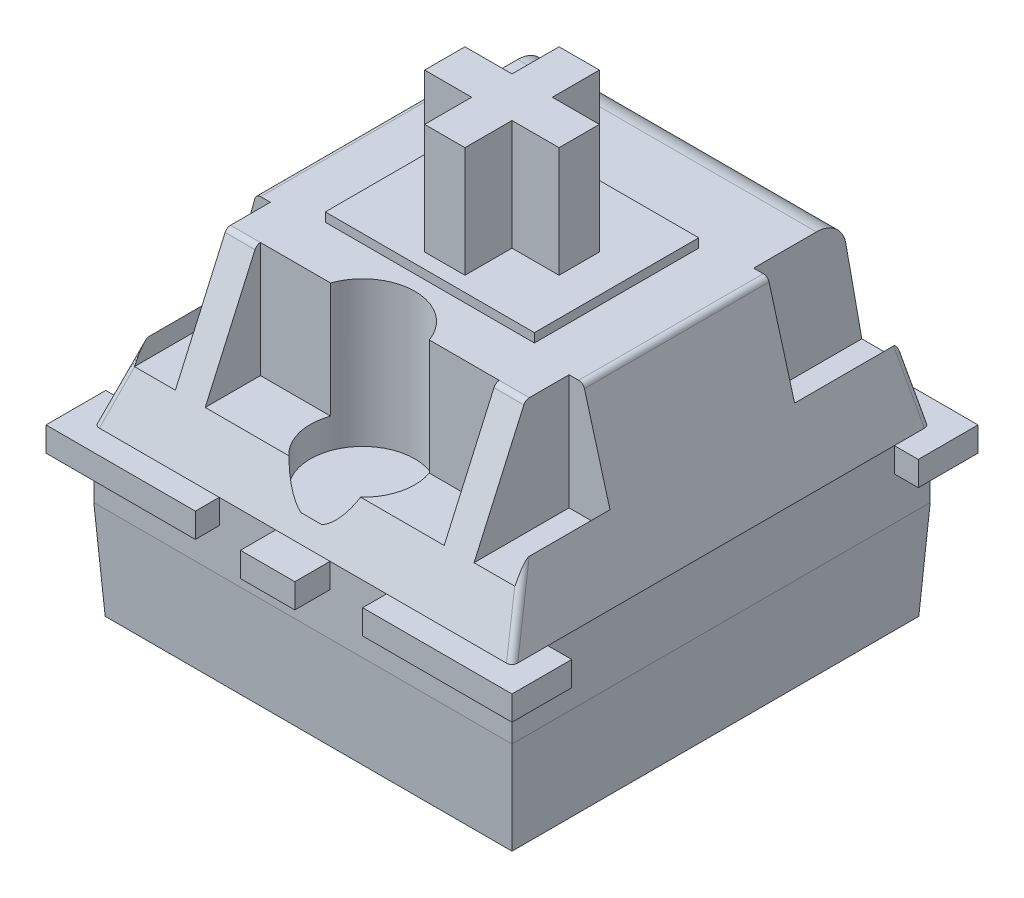
SolidWorks part; units mm, degrees
ref_plane "Front Plane" through (0, 0, 0) normal (0, 0, 1) x (1, 0, 0)
ref_plane "Top Plane" through (0, 0, 0) normal (0, 1, 0) x (1, 0, 0)
ref_plane "Right Plane" through (0, 0, 0) normal (1, 0, 0) x (0, 0, -1)
sketch "Sketch1" plane through (0, 0, 0) normal (0, 1, 0) x (1, 0, 0)
  line L1 (-7, -7) -> (7, -7)
  line L2 (-7, -7) -> (-7, 7)
  line L3 (-7, 7) -> (7, 7)
  line L4 (7, -7) -> (7, 7)
  line L5 (-7, -7) -> (7, 7) construction
  line L6 (-7, 7) -> (7, -7) construction
  point P0 (0, 0)
  dimension "D1" = 14
extrude "Boss-Extrude1" add sketch "Sketch1" against normal blind 2.25
sketch "Sketch2" plane through (0, -2.25, 0) normal (0, -1, 0) x (1, 0, 0)
  line L8 (7, -7) -> (7, 7)
  line L9 (7, 7) -> (-7, 7)
  line L10 (-7, 7) -> (-7, -7)
  line L11 (-7, -7) -> (7, -7)
  line L12 (7, -7) -> (7, 7)
  line L13 (7, 7) -> (-7, 7)
  line L14 (-7, 7) -> (-7, -7)
  line L15 (-7, -7) -> (7, -7)
  dimension "D1" = 0
extrude "Boss-Extrude2" add sketch "Sketch2" along normal blind 3.3 draft 3.3
sketch "Sketch3" plane through (0, -5.55, 0) normal (0, -1, 0) x (1, 0, 0)
  circle A0 centre (0, 0) radius 1.925
  dimension "D1" = 3.85
extrude "Boss-Extrude3" add sketch "Sketch3" along normal blind 3.3
chamfer "Chamfer1" distance 0.69 distance2 0.4 1 edges at (0, -8.85, -1.925)
sketch "Sketch4" plane through (0, -5.55, 0) normal (0, -1, 0) x (1, 0, 0)
  line L10 (-4.24, -2.64) -> (-3.38, -2.64)
  line L11 (-4.24, -2.64) -> (-4.24, -2.44)
  line L12 (-4.24, -2.44) -> (-3.38, -2.44)
  line L13 (-3.38, -2.64) -> (-3.38, -2.44)
  line L14 (-4.24, -2.64) -> (-3.38, -2.44) construction
  line L15 (-4.24, -2.44) -> (-3.38, -2.64) construction
  line L16 (2.11, -5.18) -> (2.97, -5.18)
  line L17 (2.11, -5.18) -> (2.11, -4.98)
  line L18 (2.11, -4.98) -> (2.97, -4.98)
  line L19 (2.97, -5.18) -> (2.97, -4.98)
  line L20 (2.11, -5.18) -> (2.97, -4.98) construction
  line L21 (2.11, -4.98) -> (2.97, -5.18) construction
  point P0 (-3.81, -2.54)
  point P5 (2.54, -5.08)
  dimension "D1" = 0.86
  dimension "D2" = 0.2
  dimension "D3" = 3.81
  dimension "D4" = 2.54
  dimension "D5" = 5.08
  dimension "D6" = 2.54
extrude "Boss-Extrude4" add sketch "Sketch4" along normal blind 3.3
sketch "Sketch5" plane through (0, 0, 0) normal (0, 1, 0) x (1, 0, 0)
  line L0 (0, 7) -> (0, 8.18) construction
  line L1 (7, 7) -> (-7, 7) construction
  line L2 (0.91, 8.18) -> (-0.91, 8.18)
  line L3 (-0.91, 8.18) -> (-0.91, 7)
  line L4 (-0.91, 7) -> (0.91, 7)
  line L5 (-2.8, 7) -> (-2.8, 7.8)
  line L6 (-2.8, 7.8) -> (-7.8, 7.8)
  line L7 (-7.8, 7.8) -> (-7.8, 5.8)
  line L8 (-7.8, 5.8) -> (-7, 5.8)
  line L9 (-7, 7) -> (-7, -7) construction
  line L10 (-7, 5.8) -> (-7, 7)
  line L11 (-7, 7) -> (-2.8, 7)
  line L12 (-7, 0) -> (7, 0) construction
  line L13 (7, -7) -> (7, 7) construction
  line L14 (0, 7) -> (0, -7) construction
  line L15 (-7, -7) -> (7, -7) construction
  line L16 (7, 7) -> (2.8, 7)
  line L17 (7, 5.8) -> (7, 7)
  line L18 (7.8, 5.8) -> (7, 5.8)
  line L19 (7.8, 7.8) -> (7.8, 5.8)
  line L20 (2.8, 7.8) -> (7.8, 7.8)
  line L21 (2.8, 7) -> (2.8, 7.8)
  line L22 (0.91, 8.18) -> (0.91, 7)
  line L23 (0.91, -8.18) -> (0.91, -7)
  line L24 (2.8, -7) -> (2.8, -7.8)
  line L25 (2.8, -7.8) -> (7.8, -7.8)
  line L26 (7.8, -7.8) -> (7.8, -5.8)
  line L27 (7.8, -5.8) -> (7, -5.8)
  line L28 (7, -5.8) -> (7, -7)
  line L29 (7, -7) -> (2.8, -7)
  line L30 (-7, -7) -> (-2.8, -7)
  line L31 (-7, -5.8) -> (-7, -7)
  line L32 (-7.8, -5.8) -> (-7, -5.8)
  line L33 (-7.8, -7.8) -> (-7.8, -5.8)
  line L34 (-2.8, -7.8) -> (-7.8, -7.8)
  line L35 (-2.8, -7) -> (-2.8, -7.8)
  line L36 (-0.91, -7) -> (0.91, -7)
  line L37 (-0.91, -8.18) -> (-0.91, -7)
  line L38 (0.91, -8.18) -> (-0.91, -8.18)
  point P23 (-7.9002, 7.7122)
  dimension "D1" = 5
  dimension "D2" = 2
  dimension "D3" = 15.6
  dimension "D4" = 1.18
  dimension "D5" = 1.82
extrude "Boss-Extrude5" add sketch "Sketch5" against normal blind 0.82
sketch "Sketch6" plane through (7, 0, 0) normal (1, 0, 0) x (0, 0, -1)
  line L4 (7, 0) -> (6.0302, 5.5)
  line L5 (5.8, 0) -> (7.8, 0) construction
  line L6 (6.0302, 5.5) -> (-4.5512, 5.5)
  line L7 (-4.5512, 5.5) -> (-7, 0)
  line L8 (-7.8, 0) -> (-5.8, 0) construction
  line L9 (-7, -2.25) -> (-7, -0.82) construction
  line L10 (7, -2.25) -> (7, -0.82) construction
  line L11 (-5.8, 0) -> (5.8, 0) construction
  line L13 (-7, 0) -> (7, 0)
  dimension "D1" = 5.5
  dimension "D2" = 66
  dimension "D3" = 80
extrude "Boss-Extrude6" add sketch "Sketch6" against normal up to surface (14 mm away) up to face at (-7, -0.9725, 0)
sketch "Sketch8" plane through (0, 0, 7) normal (0, 0, 1) x (1, 0, 0)
  line L0 (-7, 0) -> (0, 0) construction
  line L1 (0, 0) -> (0, 5.5) construction
  line L2 (0, 5.5) -> (-5.4747, 5.5) construction
  line L3 (-5.4747, 5.5) -> (-7, 0)
  line L4 (-7, 0) -> (-7, 5.5)
  line L5 (-7, 5.5) -> (-5.4747, 5.5)
  line L10 (-7, 5.5) -> (-7, 0) construction
  line L11 (-7, 5.5) -> (7, 5.5) construction
  line L12 (-7, -2.25) -> (-7, -0.82) construction
  line L13 (7, 5.5) -> (5.4747, 5.5)
  line L14 (7, 0) -> (7, 5.5)
  line L15 (5.4747, 5.5) -> (7, 0)
  point P2 (0, 0)
  point P5 (0, 0)
  point P8 (0, 0)
  point P10 (0, 0)
  point P12 (-7, 0)
  point P13 (0, 0)
  point P14 (0, 0)
  point P15 (0, 0)
  point P19 (-7, 5.45)
  dimension "D1" = 15.5
extrude "Cut-Extrude2" cut sketch "Sketch8" against normal up to surface (14 mm away)
fillet "Fillet1" radius 1 1 edges at (0, 5.5, -6.0302)
fillet "Fillet2" radius 0.2 9 edges at (-6.3519, 2.3368, -6.588) (-5.5396, 5.266, -5.8339) (6.3519, 2.3368, -6.588) (5.5396, 5.266, -5.8339) (-6.2374, 2.75, 5.7756) (-5.4747, 5.5, -0.3199) (0, 5.5, 4.5512) (6.2374, 2.75, 5.7756) (5.4747, 5.5, -0.3199)
sketch "Sketch9" plane through (0, 5.5, 0) normal (0, 1, 0) x (1, 0, 0)
  line L0 (-7, 5.8) -> (-7, -5.8) construction
  line L1 (-6.37, 3.09) -> (-5, 3.09)
  line L2 (-6.37, 3.09) -> (-6.37, 7)
  line L3 (-6.37, 7) -> (-5, 7)
  line L4 (-5, 3.09) -> (-5, 7)
  line L5 (-6.8021, 7) -> (-2.8, 7) construction
  line L6 (0, 7) -> (0, -7) construction
  line L7 (-0.91, 7) -> (0.91, 7) construction
  line L8 (-0.91, -7) -> (0.91, -7) construction
  line L9 (-7, 0) -> (7, 0) construction
  line L10 (7, 5.8) -> (7, -5.8) construction
  line L11 (5, 3.09) -> (5, 7)
  line L12 (6.37, 7) -> (5, 7)
  line L13 (6.37, 3.09) -> (6.37, 7)
  line L14 (6.37, 3.09) -> (5, 3.09)
  line L15 (6.37, -3.09) -> (5, -3.09)
  line L16 (6.37, -3.09) -> (6.37, -7)
  line L17 (6.37, -7) -> (5, -7)
  line L18 (5, -3.09) -> (5, -7)
  line L19 (-5, -3.09) -> (-5, -7)
  line L20 (-6.37, -7) -> (-5, -7)
  line L21 (-6.37, -3.09) -> (-6.37, -7)
  line L22 (-6.37, -3.09) -> (-5, -3.09)
  line L24 (-6.815, -7) -> (-2.8, -7) construction
  line L25 (-4, -7) -> (4, -7)
  line L26 (-4, -7) -> (-4, -4.4214)
  line L27 (-4, -4.4214) -> (4, -4.4214)
  line L28 (4, -7) -> (4, -4.4214)
  line L29 (-5.3226, -4.4214) -> (5.3226, -4.4214) construction
  point P41 (0, -4.4214)
  dimension "D1" = 1.37
  dimension "D2" = 6.18
  dimension "D3" = 10
  dimension "D4" = 8
extrude "Cut-Extrude3" cut sketch "Sketch9" against normal blind 3.86
sketch "Sketch10" plane through (0, 5.5, 0) normal (0, 1, 0) x (1, 0, 0)
  line L0 (0.91, -7) -> (2.8, -7) construction
  circle A0 centre (0, -5) radius 1.75
  point P4 (0, 0)
  dimension "D1" = 3.5
  dimension "D2" = 2
extrude "Cut-Extrude4" cut sketch "Sketch10" against normal blind 4.86
sketch "Sketch11" plane through (0, 5.5, 0) normal (0, 1, 0) x (1, 0, 0)
  line L0 (0.675, -0.675) -> (-0.675, 0.675) construction
  line L1 (0.675, -2.25) -> (-0.675, -2.25)
  line L2 (0.675, -2.25) -> (0.675, -0.675)
  line L3 (0.675, 2.25) -> (-0.675, 2.25)
  line L4 (-0.675, -2.25) -> (-0.675, -0.675)
  line L5 (0.675, 0.675) -> (2.25, 0.675)
  line L6 (0.675, 0.675) -> (0.675, 2.25)
  line L7 (-2.25, 0.675) -> (-0.675, 0.675)
  line L8 (-2.25, 0.675) -> (-2.25, -0.675)
  line L9 (-2.25, -0.675) -> (-0.675, -0.675)
  line L10 (2.25, 0.675) -> (2.25, -0.675)
  line L11 (-0.675, 0.675) -> (-0.675, 2.25)
  line L12 (0.675, -0.675) -> (2.25, -0.675)
  dimension "D1" = 4.5
  dimension "D2" = 1.35
extrude "Boss-Extrude7" add sketch "Sketch11" along normal blind 4
sketch "Sketch12" plane through (0, 5.5, 0) normal (0, 1, 0) x (1, 0, 0)
  line L1 (-3.5, -2.75) -> (3.5, -2.75)
  line L2 (-3.5, -2.75) -> (-3.5, 2.75)
  line L3 (-3.5, 2.75) -> (3.5, 2.75)
  line L4 (3.5, -2.75) -> (3.5, 2.75)
  line L5 (-3.5, -2.75) -> (3.5, 2.75) construction
  line L6 (-3.5, 2.75) -> (3.5, -2.75) construction
  point P0 (0, 0)
  dimension "D1" = 5.5
  dimension "D2" = 7
extrude "Boss-Extrude8" add sketch "Sketch12" along normal blind 0.3
